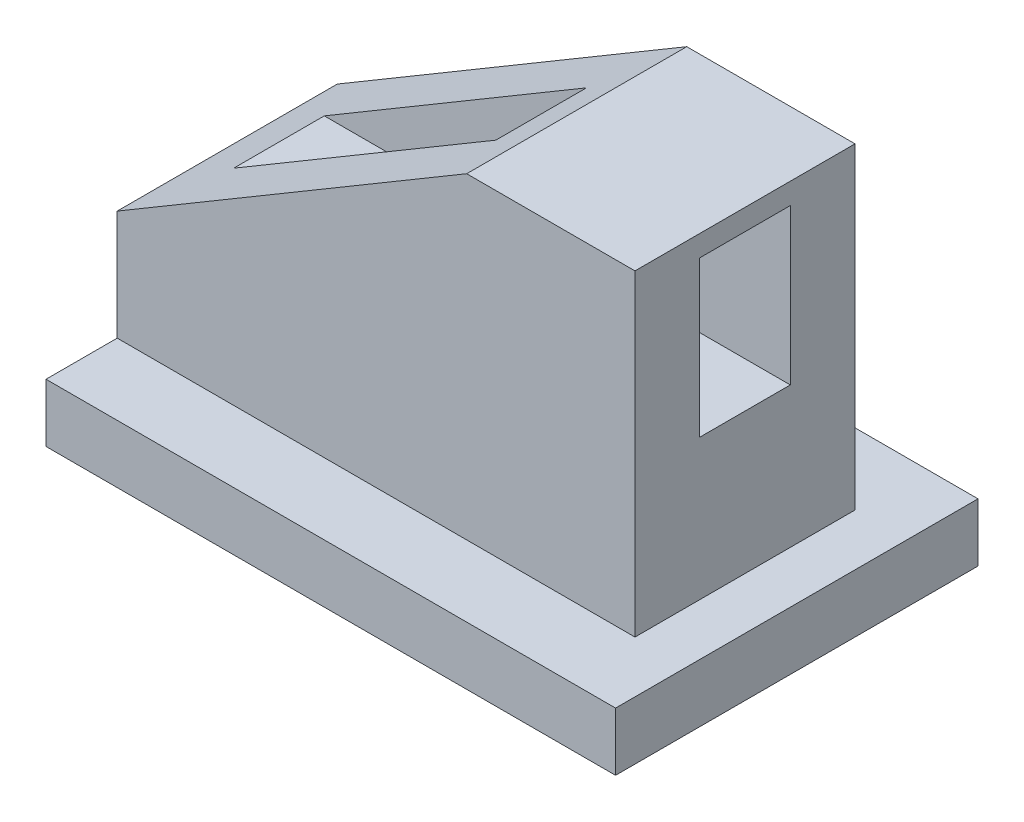
SolidWorks part; units mm, degrees
ref_plane "Front Plane" through (0, 0, 0) normal (0, 0, 1) x (1, 0, 0)
ref_plane "Top Plane" through (0, 0, 0) normal (0, 1, 0) x (1, 0, 0)
ref_plane "Right Plane" through (0, 0, 0) normal (1, 0, 0) x (0, 0, -1)
sketch "Sketch1" plane through (0, 0, 0) normal (0, 1, 0) x (1, 0, 0)
  line L1 (-44, -28) -> (44, -28)
  line L2 (-44, -28) -> (-44, 28)
  line L3 (-44, 28) -> (44, 28)
  line L4 (44, -28) -> (44, 28)
  line L5 (-44, -28) -> (44, 28) construction
  line L6 (-44, 28) -> (44, -28) construction
  point P0 (0, 0)
  dimension "D1" = 88
  dimension "D2" = 56
extrude "Boss-Extrude1" add sketch "Sketch1" along normal blind 9
ref_plane "Plane1" through (0, 0, 17) normal (0, 0, 1) x (1, 0, 0)
sketch "Sketch2" plane through (0, 0, 17) normal (0, 0, 1) x (1, 0, 0)
  line L0 (-44, 9) -> (36, 9)
  line L1 (-44, 9) -> (44, 9) construction
  line L2 (36, 9) -> (36, 58)
  line L3 (36, 58) -> (10, 58)
  line L4 (10, 58) -> (-44, 26)
  line L5 (-44, 26) -> (-44, 9)
  line L6 (-44, 0) -> (44, 0) construction
  dimension "D1" = 80
  dimension "D2" = 49
  dimension "D3" = 26
  dimension "D4" = 26
extrude "Boss-Extrude2" add sketch "Sketch2" against normal blind 34
sketch "Sketch3" plane through (36, 0, 0) normal (1, 0, 0) x (0, 0, -1)
  line L1 (-7, 30.74) -> (7, 30.74)
  line L2 (-7, 30.74) -> (-7, 54.74)
  line L3 (-7, 54.74) -> (7, 54.74)
  line L4 (7, 30.74) -> (7, 54.74)
  line L5 (-7, 30.74) -> (7, 54.74) construction
  line L6 (-7, 54.74) -> (7, 30.74) construction
  line L7 (0, 0) -> (0, 58) construction
  line L8 (17, 58) -> (-17, 58) construction
  point P0 (0, 42.74)
  point P5 (7, 46.5807)
  point P6 (-7, 53.2528)
  point P12 (-7, 52.5393)
  point P13 (-7, 31.6133)
  dimension "D1" = 14
  dimension "D2" = 4.74
  dimension "D3" = 24
extrude "Cut-Extrude1" cut sketch "Sketch3" against normal through all
